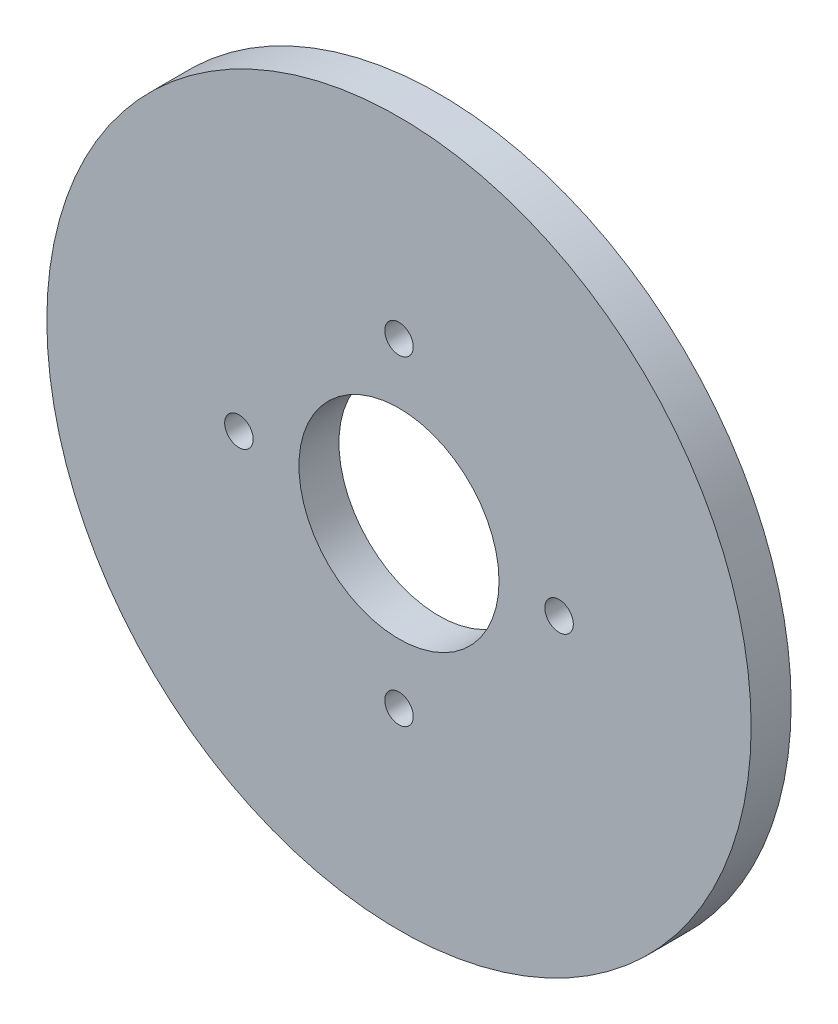
SolidWorks part; units mm, degrees
ref_plane "Front Plane" through (0, 0, 0) normal (0, 0, 1) x (1, 0, 0)
ref_plane "Top Plane" through (0, 0, 0) normal (0, 1, 0) x (1, 0, 0)
ref_plane "Right Plane" through (0, 0, 0) normal (1, 0, 0) x (0, 0, -1)
sketch "Sketch1" plane through (0, 0, 0) normal (0, 0, 1) x (1, 0, 0)
  circle A0 centre (0, 0) radius 27.94
  circle A1 centre (0, 0) radius 7.9375
  dimension "D1" = 55.88
  dimension "D2" = 15.875
extrude "Boss-Extrude1" add sketch "Sketch1" along normal blind 3.175
hole_wizard "Tap Drill for #4-40 Tap1" positions "Sketch2" profile "Sketch3" hole size "#4-40" standard "ANSI Inch"
sketch "Sketch2" plane through (0, 0, 3.175) normal (0, 0, 1) x (1, 0, 0)
  point P0 (0, 12.7)
  point P2 (0, -12.7)
  point P4 (12.7, 0)
  point P6 (-12.7, 0)
  dimension "D1" = 12.7
  dimension "D2" = 12.7
  dimension "D3" = 12.7
  dimension "D4" = 12.7
sketch "Sketch3" plane through (0, 12.7, 3.175) normal (1, 0, 0) x (0, -1, 0)
  line L0 (0, 0) -> (0, 4.6792)
  line L1 (0, 4.6792) -> (1.1303, 4)
  line L2 (1.1303, 4) -> (1.1303, 0)
  line L5 (1.1303, 0) -> (0, 0)
  line L10 (0, 4.6792) -> (-1.1303, 4) construction
  line L11 (0, -6.35) -> (0, 107.95) construction
  dimension "Hole Dia." = 2.2606
  dimension "Hole Depth" = 4
  dimension "Drill Angle" = 118
